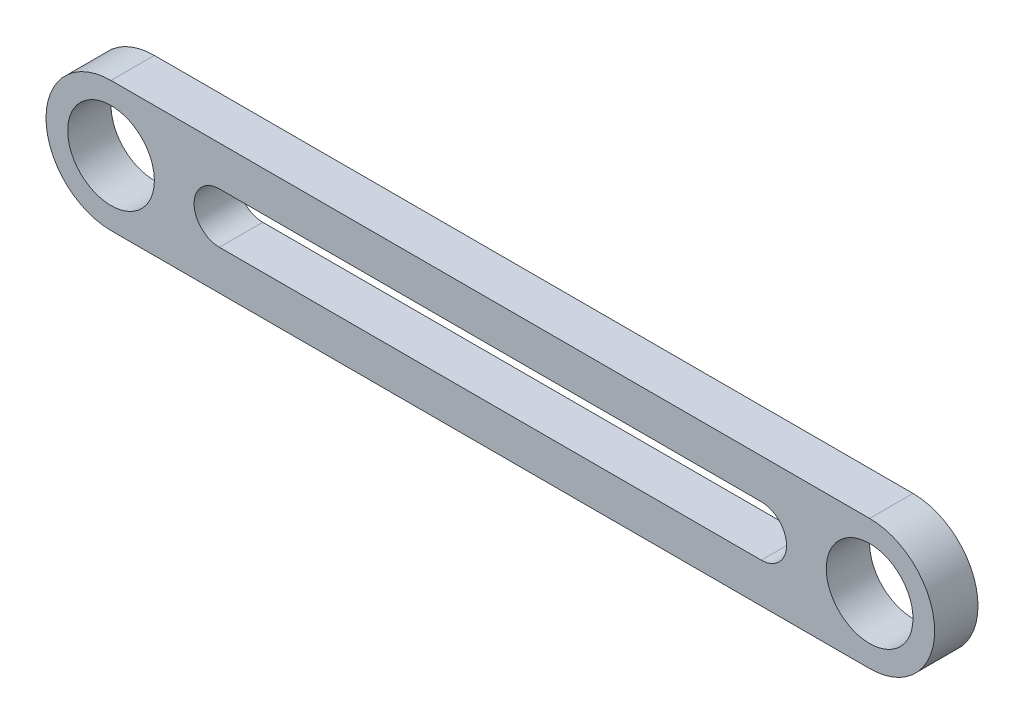
SolidWorks part; units mm, degrees
material "Thornel Mat VMA"
ref_plane "前视基准面" through (0, 0, 0) normal (0, 0, 1) x (1, 0, 0)
ref_plane "上视基准面" through (0, 0, 0) normal (0, 1, 0) x (1, 0, 0)
ref_plane "右视基准面" through (0, 0, 0) normal (1, 0, 0) x (0, 0, -1)
sketch "草图1" plane through (0, 0, 0) normal (0, 0, 1) x (1, 0, 0)
  line L0 (0, 0) -> (105, 0) construction
  line L1 (0, 0) -> (105, 0) construction
  line L2 (0, 9) -> (105, 9)
  line L3 (0, -9) -> (105, -9)
  circle A0 centre (0, 0) radius 6
  circle A1 centre (105, 0) radius 6
  arc A2 (0, 9) -> (0, -9) centre (0, 0) ccw
  arc A3 (105, -9) -> (105, 9) centre (105, 0) ccw
  point P5 (52.5, 0)
  dimension "D1" = 12
  dimension "D3" = 9
  dimension "D4" = 12
  dimension "D2" = 105
extrude "凸台-拉伸1" add sketch "草图1" along normal blind 6
sketch "草图2" plane through (0, 0, 6) normal (0, 0, 1) x (1, 0, 0)
  line L0 (15, 0) -> (90, 0) construction
  line L5 (15, 3.5) -> (90, 3.5)
  line L6 (15, -3.5) -> (90, -3.5)
  line L7 (52.5, 0) -> (52.5, 9) construction
  line L8 (105, 9) -> (0, 9) construction
  arc A6 (15, 3.5) -> (15, -3.5) centre (15, 0) ccw
  arc A7 (90, -3.5) -> (90, 3.5) centre (90, 0) ccw
  point P4 (52.5, 0)
  dimension "D2" = 15
  dimension "D1" = 3.5
extrude "切除-拉伸1" cut sketch "草图2" against normal blind 10
